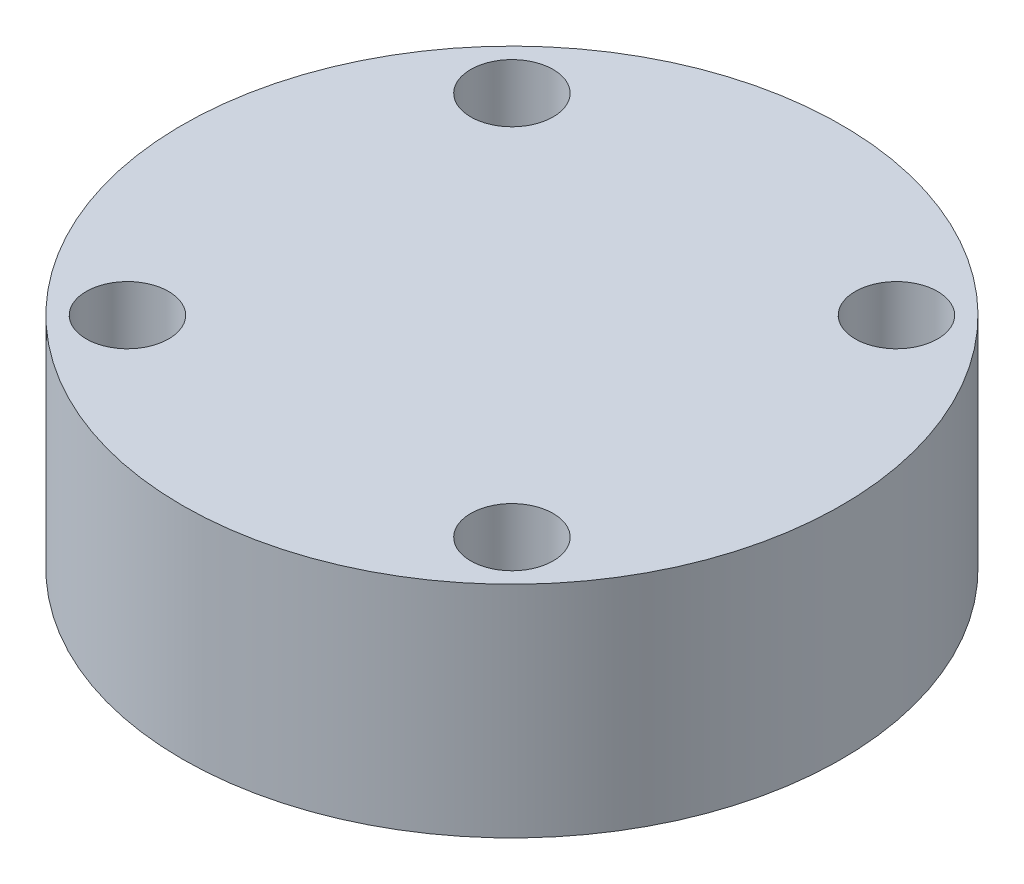
SolidWorks part; units mm, degrees
ref_plane "Front Plane" through (0, 0, 0) normal (0, 0, 1) x (1, 0, 0)
ref_plane "Top Plane" through (0, 0, 0) normal (0, 1, 0) x (1, 0, 0)
ref_plane "Right Plane" through (0, 0, 0) normal (1, 0, 0) x (0, 0, -1)
sketch "Sketch1" plane through (0, 0, 0) normal (0, 1, 0) x (1, 0, 0)
  line L0 (0, 0) -> (5.5562, 0) construction
  line L1 (5.5562, 0) -> (5.5562, 5.5562) construction
  line L2 (0, 0) -> (0, 4.9808) construction
  circle A0 centre (0, 0) radius 9.525
  circle A1 centre (5.5562, 5.5562) radius 1.1906
  circle A2 centre (5.5562, -5.5562) radius 1.1906
  circle A3 centre (-5.5562, -5.5562) radius 1.1906
  circle A4 centre (-5.5562, 5.5562) radius 1.1906
extrude "Boss-Extrude1" add sketch "Sketch1" along normal blind 6.35
